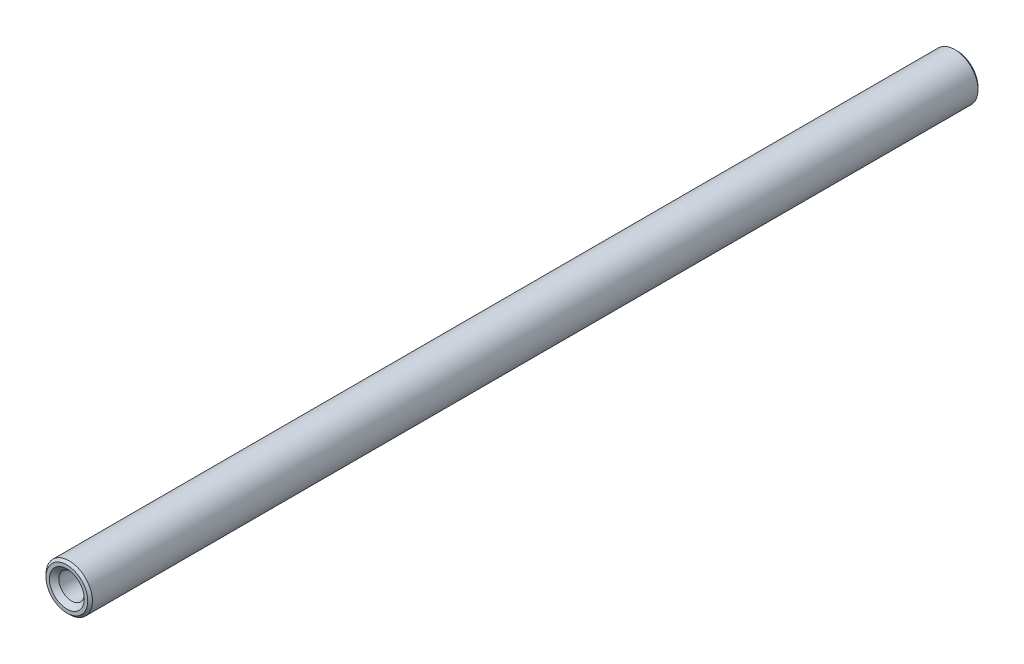
SolidWorks part; units mm, degrees
material "AISI 304"
ref_plane "Front" through (0, 0, 0) normal (0, 0, 1) x (1, 0, 0)
ref_plane "Top" through (0, 0, 0) normal (0, 1, 0) x (1, 0, 0)
ref_plane "Right" through (0, 0, 0) normal (1, 0, 0) x (0, 0, -1)
sketch "Диаметр детали" plane through (0, 0, 0) normal (0, 0, 1) x (1, 0, 0)
  circle A0 centre (0, 0) radius 3
  dimension "D1" = 6
extrude "Длина детали" add sketch "Диаметр детали" along normal blind 115
hole_wizard "Отверстие обработанное метчиком M41" positions "Эскиз1" profile "Эскиз2" tap size "M4" standard "DIN"
sketch "Эскиз1" plane through (0, 0, 115) normal (0, 0, 1) x (1, 0, 0)
  point P0 (0, 0)
sketch "Эскиз2" plane through (0, 0, 115) normal (1, 0, 0) x (0, -1, 0)
  line L0 (0, 0) -> (0, 12.9914)
  line L1 (0, 12.9914) -> (1.65, 12)
  line L2 (1.65, 12) -> (1.65, 0.6)
  line L3 (1.65, 0.6) -> (2.25, 0)
  line L5 (2.25, 0) -> (0, 0)
  line L6 (-1.65, 0.6) -> (-2.25, 0) construction
  line L10 (0, 12.9914) -> (-1.65, 12) construction
  line L11 (0, -6.35) -> (0, 107.95) construction
  dimension "Диаметр сверла" = 3.3
  dimension "Глубина сверла" = 12
  dimension "Диаметр передней зенковки" = 4.5
  dimension "Угол передней зенковки" = 90
  dimension "Угол заточки сверла" = 118
cosmetic thread "Отверстие резьбы1" parameters "D1"=9.3, "D2"=4
hole_wizard "Отверстие обработанное метчиком M42" positions "Эскиз3" profile "Эскиз4" tap size "M4" standard "DIN"
sketch "Эскиз3" plane through (0, 0, 0) normal (0, 0, -1) x (-1, 0, 0)
  point P0 (0, 0)
sketch "Эскиз4" plane through (0, 0, 0) normal (1, 0, 0) x (0, 1, 0)
  line L0 (0, 0) -> (0, 12.9914)
  line L1 (0, 12.9914) -> (1.65, 12)
  line L2 (1.65, 12) -> (1.65, 0.6)
  line L3 (1.65, 0.6) -> (2.25, 0)
  line L5 (2.25, 0) -> (0, 0)
  line L6 (-1.65, 0.6) -> (-2.25, 0) construction
  line L10 (0, 12.9914) -> (-1.65, 12) construction
  line L11 (0, -6.35) -> (0, 107.95) construction
  dimension "Диаметр сверла" = 3.3
  dimension "Глубина сверла" = 12
  dimension "Диаметр передней зенковки" = 4.5
  dimension "Угол передней зенковки" = 90
  dimension "Угол заточки сверла" = 118
cosmetic thread "Отверстие резьбы2" parameters "D1"=9.3, "D2"=4
chamfer "Фаска1" distance 0.3 angle 45 2 edges at (3, 0, 0) (3, 0, 115)
